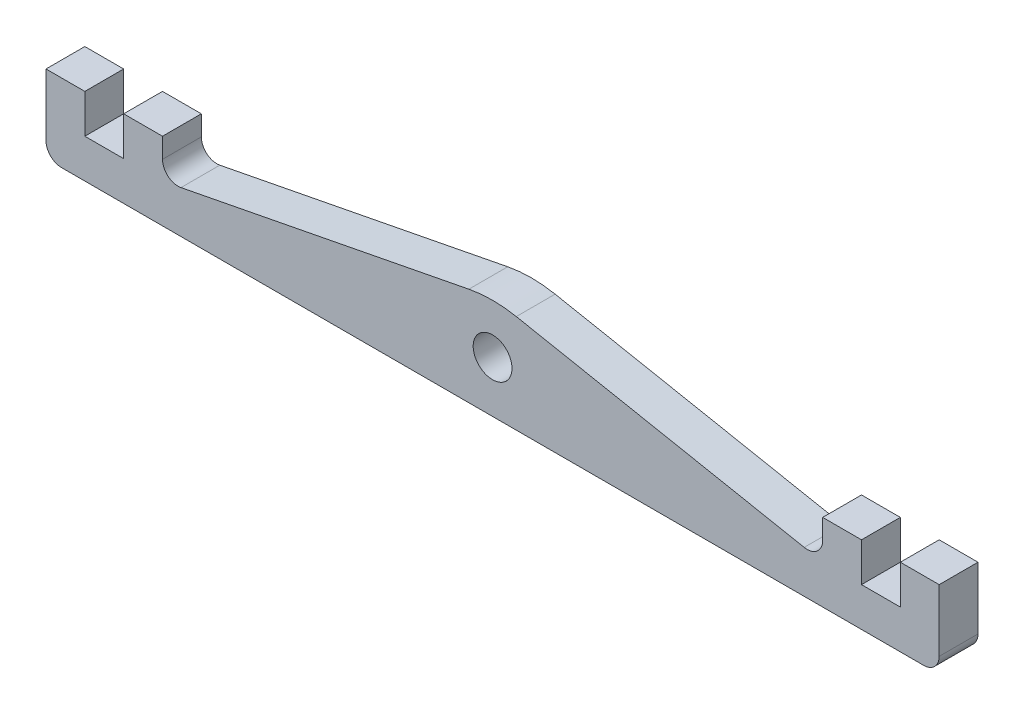
SolidWorks part; units mm, degrees
ref_plane "Front Plane" through (0, 0, 0) normal (0, 0, 1) x (1, 0, 0)
ref_plane "Top Plane" through (0, 0, 0) normal (0, 1, 0) x (1, 0, 0)
ref_plane "Right Plane" through (0, 0, 0) normal (1, 0, 0) x (0, 0, -1)
sketch "Sketch2" plane through (0, 0, 0) normal (0, 0, 1) x (1, 0, 0)
  line L0 (-3.8772, 18.628) -> (-50.9503, 9.4779)
  line L1 (-53.975, 11.9713) -> (-53.975, 15.24)
  line L2 (-53.975, 15.24) -> (-60.325, 15.24)
  line L3 (-60.325, 15.24) -> (-60.325, 8.89)
  line L4 (-60.325, 8.89) -> (-66.675, 8.89)
  line L5 (-66.675, 8.89) -> (-66.675, 15.24)
  line L6 (-66.675, 15.24) -> (-73.025, 15.24)
  line L7 (-73.025, 15.24) -> (-73.025, 5.08)
  line L8 (0, 10.922) -> (0, 2.54) construction
  line L9 (-60.325, 8.89) -> (0, 8.89) construction
  line L10 (-70.485, 2.54) -> (70.485, 2.54)
  line L11 (73.025, 15.24) -> (73.025, 5.08)
  line L12 (66.675, 15.24) -> (73.025, 15.24)
  line L13 (66.675, 8.89) -> (66.675, 15.24)
  line L14 (60.325, 8.89) -> (66.675, 8.89)
  line L15 (60.325, 15.24) -> (60.325, 8.89)
  line L16 (53.975, 15.24) -> (60.325, 15.24)
  line L17 (53.975, 11.9713) -> (53.975, 15.24)
  line L18 (3.8772, 18.628) -> (50.9503, 9.4779)
  line L19 (0, 2.54) -> (0, 0) construction
  line L21 (0, 10.922) -> (0, 19.3817) construction
  line L22 (-50.9503, 9.4779) -> (-53.975, 8.89) construction
  line L23 (-53.975, 11.9713) -> (-53.975, 8.89) construction
  circle A0 centre (0, 10.922) radius 3.175
  arc A1 (70.485, 2.54) -> (73.025, 5.08) centre (70.485, 5.08) ccw
  arc A2 (50.9503, 9.4779) -> (53.975, 11.9713) centre (51.435, 11.9713) ccw
  arc A3 (-50.9503, 9.4779) -> (-53.975, 11.9713) centre (-51.435, 11.9713) cw
  circle A4 centre (0, 10.922) radius 10.922 construction
  arc A5 (-70.485, 2.54) -> (-73.025, 5.08) centre (-70.485, 5.08) cw
  arc A6 (3.8772, 18.628) -> (-3.8772, 18.628) centre (0, -1.3186) ccw
  dimension "D2" = 6.35
  dimension "D3" = 133.35
  dimension "D8" = 11
  dimension "D9" = 2.54
  dimension "D10" = 21.844
  dimension "D12" = 2.54
  dimension "D7" = 2.54
  dimension "D13" = 20.32
  dimension "D1" = 6.35
  dimension "D4" = 6.35
  dimension "D5" = 6.35
  dimension "D6" = 6.35
  dimension "D11" = 6.35
extrude "Extrude1" add sketch "Sketch2" along normal blind 6.35
